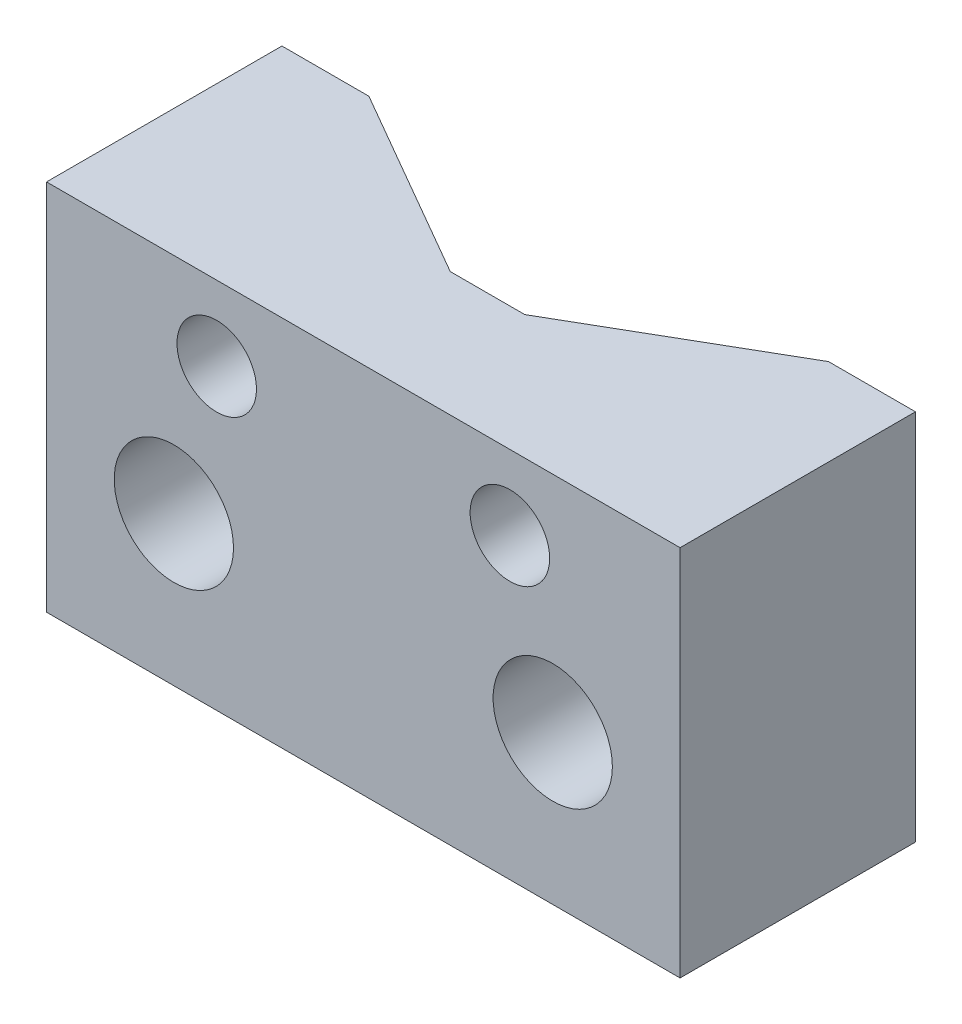
SolidWorks part; units mm, degrees
ref_plane "Front Plane" through (0, 0, 0) normal (0, 0, 1) x (1, 0, 0)
ref_plane "Top Plane" through (0, 0, 0) normal (0, 1, 0) x (1, 0, 0)
ref_plane "Right Plane" through (0, 0, 0) normal (1, 0, 0) x (0, 0, -1)
sketch "Sketch1" plane through (0, 0, 0) normal (0, 1, 0) x (1, 0, 0)
  line L0 (0, 0) -> (0, -36.9932) construction
  line L1 (0, 0) -> (10.25, 0)
  line L2 (0, 0) -> (-10.25, 0)
  line L6 (0, 5) -> (1.5, 5)
  line L7 (0, 5) -> (-1.5, 5)
  line L9 (1.5, 5) -> (9.25, 9.4745)
  line L14 (-1.5, 5) -> (-9.25, 9.4745)
  line L16 (-9.25, 9.4745) -> (-12.75, 9.4745)
  line L18 (-10.25, 0) -> (-12.75, 0)
  line L19 (-12.75, 9.4745) -> (-12.75, 0)
  line L20 (9.25, 9.4745) -> (12.75, 9.4745)
  line L22 (10.25, 0) -> (12.75, 0)
  line L23 (12.75, 9.4745) -> (12.75, 0)
  dimension "D1" = 10.25
  dimension "D2" = 1.5
  dimension "D3" = 30
  dimension "D4" = 2.5
  dimension "D5" = 2.5
  dimension "D6" = 30
  dimension "D7" = 5
extrude "Boss-Extrude1" add sketch "Sketch1" along normal blind 15
sketch "Sketch2" plane through (0, 0, 0) normal (0, 0, 1) x (1, 0, 0)
  line L0 (0, 13) -> (0, -1.0111) construction
  line L2 (0, 12) -> (5.9, 12)
  line L3 (0, 12) -> (-5.9, 12)
  line L4 (-12.75, 15) -> (12.75, 15) construction
  line L5 (-7.625, 6) -> (0, 6)
  line L6 (0, 6) -> (7.625, 6)
  circle A0 centre (-5.9, 12) radius 1.6
  circle A1 centre (5.9, 12) radius 1.6
  circle A2 centre (-7.625, 6) radius 2.4
  circle A3 centre (7.625, 6) radius 2.4
  dimension "D2" = 3.2
  dimension "D4" = 15.25
  dimension "D5" = 4.8
  dimension "D6" = 4.8
  dimension "D1" = 11.8
  dimension "D3" = 3
  dimension "D7" = 6
extrude "Cut-Extrude1" cut sketch "Sketch2" against normal through all
